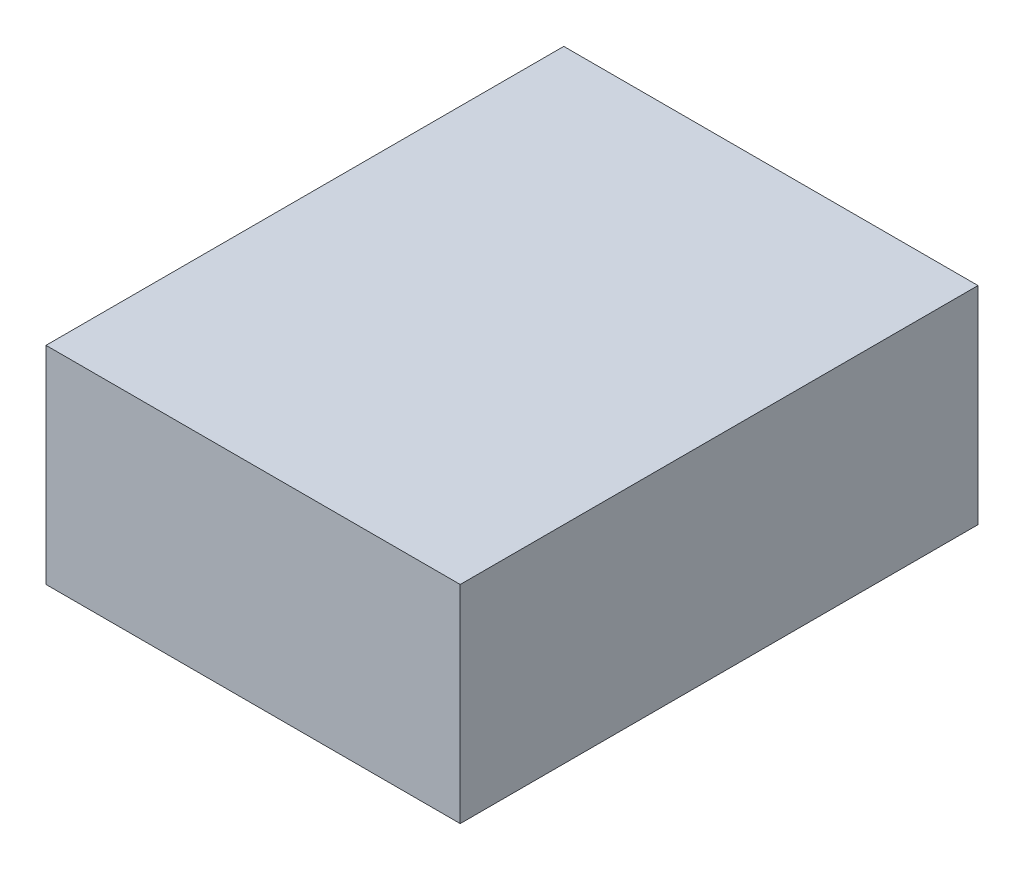
SolidWorks part; units mm, degrees
material "Pine"
ref_plane "X-Y Datum" through (0, 0, 0) normal (0, 0, 1) x (1, 0, 0)
ref_plane "X-Z Datum" through (0, 0, 0) normal (0, 1, 0) x (1, 0, 0)
ref_plane "Y-Z Datum" through (0, 0, 0) normal (1, 0, 0) x (0, 0, -1)
sketch "Sketch2" plane through (0, 0, 0) normal (0, 0, 1) x (1, 0, 0)
  line L1 (0, 0) -> (101.6, 0)
  line L2 (0, 0) -> (0, 50.8)
  line L3 (0, 50.8) -> (101.6, 50.8)
  line L4 (101.6, 0) -> (101.6, 50.8)
  dimension "D1" = 101.6
  dimension "D2" = 50.8
extrude "Boss-Extrude1" add sketch "Sketch2" along normal blind 127
